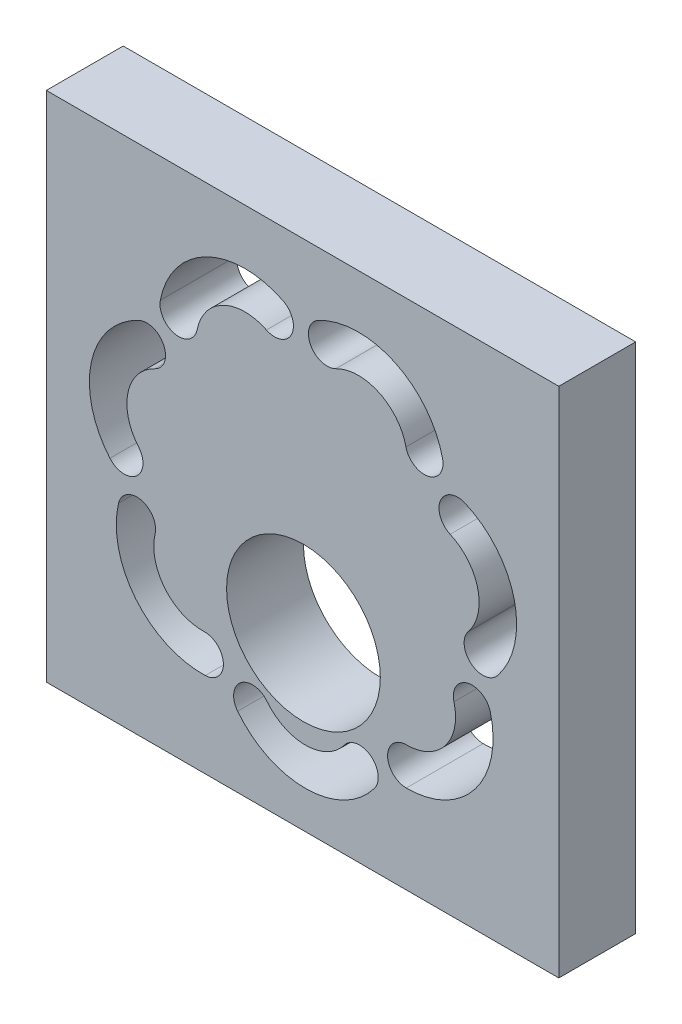
SolidWorks part; units mm, degrees
ref_plane "Front Plane" through (0, 0, 0) normal (0, 0, 1) x (1, 0, 0)
ref_plane "Top Plane" through (0, 0, 0) normal (0, 1, 0) x (1, 0, 0)
ref_plane "Right Plane" through (0, 0, 0) normal (1, 0, 0) x (0, 0, -1)
sketch "Sketch1" plane through (0, 0, 0) normal (0, 0, 1) x (1, 0, 0)
  line L1 (-20.0304, 20.0318) -> (19.9696, 20.0318)
  line L2 (-20.0304, 20.0318) -> (-20.0304, -19.9682)
  line L3 (-20.0304, -19.9682) -> (19.9696, -19.9682)
  line L4 (19.9696, 20.0318) -> (19.9696, -19.9682)
  circle A0 centre (0, 0) radius 14.7344
  circle A1 centre (0, 0) radius 12.345
  circle A2 centre (0, 0) radius 11.1503
  arc A3 (-1.7887, 11.0325) -> (-7.7524, 8.0691) centre (-3.6349, 7.2654) ccw construction
  arc A4 (-1.2757, 12.0794) -> (-8.8967, 8.2924) centre (-3.6349, 7.2654) ccw
  arc A5 (-2.3018, 9.9856) -> (-6.6081, 7.8457) centre (-3.6349, 7.2654) ccw
  arc A6 (-2.3018, 9.9856) -> (-1.2757, 12.0794) centre (-1.7887, 11.0325) ccw
  arc A7 (-8.8967, 8.2924) -> (-6.6081, 7.8457) centre (-7.7524, 8.0691) ccw
  arc A8 (7.5103, 8.2771) -> (1.4751, 11.0921) centre (3.414, 7.3718) ccw construction
  arc A9 (8.6487, 8.5287) -> (0.9363, 12.1259) centre (3.414, 7.3718) ccw
  arc A10 (6.3719, 8.0255) -> (2.0139, 10.0582) centre (3.414, 7.3718) ccw
  arc A11 (6.3719, 8.0255) -> (8.6487, 8.5287) centre (7.5103, 8.2771) ccw
  arc A12 (0.9363, 12.1259) -> (2.0139, 10.0582) centre (1.4751, 11.0921) ccw
  arc A13 (11.1539, -0.7111) -> (9.5918, 5.7625) centre (7.8921, 1.9271) ccw construction
  arc A14 (12.0604, -1.4443) -> (10.0642, 6.8284) centre (7.8921, 1.9271) ccw
  arc A15 (10.2474, 0.0221) -> (9.1195, 4.6966) centre (7.8921, 1.9271) ccw
  arc A16 (10.2474, 0.0221) -> (12.0604, -1.4443) centre (11.1539, -0.7111) ccw
  arc A17 (10.0642, 6.8284) -> (9.1195, 4.6966) centre (9.5918, 5.7625) ccw
  arc A18 (6.3984, -9.1639) -> (10.4857, -3.9064) centre (6.4273, -4.9688) ccw construction
  arc A19 (6.3904, -10.3297) -> (11.6136, -3.6111) centre (6.4273, -4.9688) ccw
  arc A20 (6.4064, -7.998) -> (9.3579, -4.2016) centre (6.4273, -4.9688) ccw
  arc A21 (6.4064, -7.998) -> (6.3904, -10.3297) centre (6.3984, -9.1639) ccw
  arc A22 (11.6136, -3.6111) -> (9.3579, -4.2016) centre (10.4857, -3.9064) ccw
  arc A23 (-3.1753, -10.716) -> (3.4836, -10.6336) centre (0.1226, -8.123) ccw construction
  arc A24 (-4.0917, -11.4367) -> (4.4177, -11.3313) centre (0.1226, -8.123) ccw
  arc A25 (-2.2588, -9.9954) -> (2.5496, -9.9359) centre (0.1226, -8.123) ccw
  arc A26 (-2.2588, -9.9954) -> (-4.0917, -11.4367) centre (-3.1753, -10.716) ccw
  arc A27 (4.4177, -11.3313) -> (2.5496, -9.9359) centre (3.4836, -10.6336) ccw
  arc A28 (-10.3579, -4.1988) -> (-6.1417, -9.3536) centre (-6.2744, -5.1605) ccw construction
  arc A29 (-11.4927, -3.9316) -> (-6.1048, -10.5188) centre (-6.2744, -5.1605) ccw
  arc A30 (-9.2231, -4.4661) -> (-6.1786, -8.1883) centre (-6.2744, -5.1605) ccw
  arc A31 (-9.2231, -4.4661) -> (-11.4927, -3.9316) centre (-10.3579, -4.1988) ccw
  arc A32 (-6.1048, -10.5188) -> (-6.1786, -8.1883) centre (-6.1417, -9.3536) ccw
  arc A33 (-9.7408, 5.4802) -> (-11.1422, -1.0301) centre (-7.9466, 1.688) ccw construction
  arc A34 (-10.2394, 6.534) -> (-12.0303, -1.7854) centre (-7.9466, 1.688) ccw
  arc A35 (-9.2422, 4.4263) -> (-10.2541, -0.2747) centre (-7.9466, 1.688) ccw
  arc A36 (-9.2422, 4.4263) -> (-10.2394, 6.534) centre (-9.7408, 5.4802) ccw
  arc A37 (-12.0303, -1.7854) -> (-10.2541, -0.2747) centre (-11.1422, -1.0301) ccw
  circle A38 centre (0, -5.1769) radius 4.7787
  point P9 (-5.5018, 11.0223)
  point P20 (5.1873, 11.1737)
  point P28 (11.9702, 2.9111)
  point P36 (9.7393, -7.5436)
  point P44 (0.1745, -12.3179)
  point P52 (-9.5217, -7.8165)
  point P60 (-12.0479, 2.5708)
  point P68 (0, 0)
  dimension "D1" = 7
  dimension "D2" = 40
  dimension "D3" = 40
extrude "Boss-Extrude1" add sketch "Sketch1" along normal blind 6 contours L1 L4 L3 L2
sketch "Sketch3" plane through (0, 0, 0) normal (0, 0, 1) x (1, 0, 0)
  arc A3 (-2.2077, 13.7407) -> (-9.6955, 10.0199) centre (-4.5257, 9.0108) ccw construction
  arc A4 (-1.5636, 15.0551) -> (-11.1322, 10.3003) centre (-4.5257, 9.0108) ccw
  arc A5 (-2.8519, 12.4262) -> (-8.2588, 9.7394) centre (-4.5257, 9.0108) ccw
  arc A6 (-2.8519, 12.4262) -> (-1.5636, 15.0551) centre (-2.2077, 13.7407) ccw
  arc A7 (-11.1322, 10.3003) -> (-8.2588, 9.7394) centre (-9.6955, 10.0199) ccw
  arc A8 (9.4678, 10.2811) -> (1.8902, 13.8154) centre (4.3246, 9.1443) ccw construction
  arc A9 (10.8972, 10.597) -> (1.2137, 15.1135) centre (4.3246, 9.1443) ccw
  arc A10 (8.0385, 9.9652) -> (2.5668, 12.5173) centre (4.3246, 9.1443) ccw
  arc A11 (8.0385, 9.9652) -> (10.8972, 10.597) centre (9.4678, 10.2811) ccw
  arc A12 (1.2137, 15.1135) -> (2.5668, 12.5173) centre (1.8902, 13.8154) ccw
  arc A13 (14.0426, -1.0042) -> (12.0813, 7.1238) centre (9.9471, 2.3081) ccw construction
  arc A14 (15.1808, -1.9248) -> (12.6744, 8.4621) centre (9.9471, 2.3081) ccw
  arc A15 (12.9045, -0.0837) -> (11.4882, 5.7855) centre (9.9471, 2.3081) ccw
  arc A16 (12.9045, -0.0837) -> (15.1808, -1.9248) centre (14.0426, -1.0042) ccw
  arc A17 (12.6744, 8.4621) -> (11.4882, 5.7855) centre (12.0813, 7.1238) ccw
  arc A18 (8.0717, -11.6173) -> (13.2036, -5.0161) centre (8.108, -6.35) ccw construction
  arc A19 (8.0617, -13.081) -> (14.6197, -4.6454) centre (8.108, -6.35) ccw
  arc A20 (8.0818, -10.1535) -> (11.7875, -5.3868) centre (8.108, -6.35) ccw
  arc A21 (8.0818, -10.1535) -> (8.0617, -13.081) centre (8.0717, -11.6173) ccw
  arc A22 (14.6197, -4.6454) -> (11.7875, -5.3868) centre (13.2036, -5.0161) ccw
  arc A23 (-3.9486, -13.5661) -> (4.412, -13.4627) centre (0.192, -10.3104) ccw construction
  arc A24 (-5.0993, -14.4709) -> (5.5848, -14.3387) centre (0.192, -10.3104) ccw
  arc A25 (-2.7979, -12.6614) -> (3.2393, -12.5866) centre (0.192, -10.3104) ccw
  arc A26 (-2.7979, -12.6614) -> (-5.0993, -14.4709) centre (-3.9486, -13.5661) ccw
  arc A27 (5.5848, -14.3387) -> (3.2393, -12.5866) centre (4.412, -13.4627) ccw
  arc A28 (-12.9669, -5.3833) -> (-7.6732, -11.8554) centre (-7.8398, -6.5907) ccw construction
  arc A29 (-14.3918, -5.0478) -> (-7.6269, -13.3185) centre (-7.8398, -6.5907) ccw
  arc A30 (-11.5421, -5.7189) -> (-7.7195, -10.3924) centre (-7.8398, -6.5907) ccw
  arc A31 (-11.5421, -5.7189) -> (-14.3918, -5.0478) centre (-12.9669, -5.3833) ccw
  arc A32 (-7.6269, -13.3185) -> (-7.7195, -10.3924) centre (-7.6732, -11.8554) ccw
  arc A33 (-12.1921, 6.7693) -> (-13.9517, -1.4047) centre (-9.9394, 2.008) ccw construction
  arc A34 (-12.8182, 8.0925) -> (-15.0667, -2.3531) centre (-9.9394, 2.008) ccw
  arc A35 (-11.5661, 5.4462) -> (-12.8367, -0.4563) centre (-9.9394, 2.008) ccw
  arc A36 (-11.5661, 5.4462) -> (-12.8182, 8.0925) centre (-12.1921, 6.7693) ccw
  arc A37 (-15.0667, -2.3531) -> (-12.8367, -0.4563) centre (-13.9517, -1.4047) ccw
  circle A38 centre (0.0381, -6.6114) radius 6
  point P9 (-6.8697, 13.7279)
  point P20 (6.5511, 13.918)
  point P28 (15.0675, 3.5437)
  point P36 (12.2665, -9.583)
  point P44 (0.2572, -15.5774)
  point P52 (-11.917, -9.9256)
  point P60 (-15.0888, 3.1165)
  point P68 (0.0381, -0.1114)
extrude "Cut-Extrude1" cut sketch "Sketch3" along normal through all
